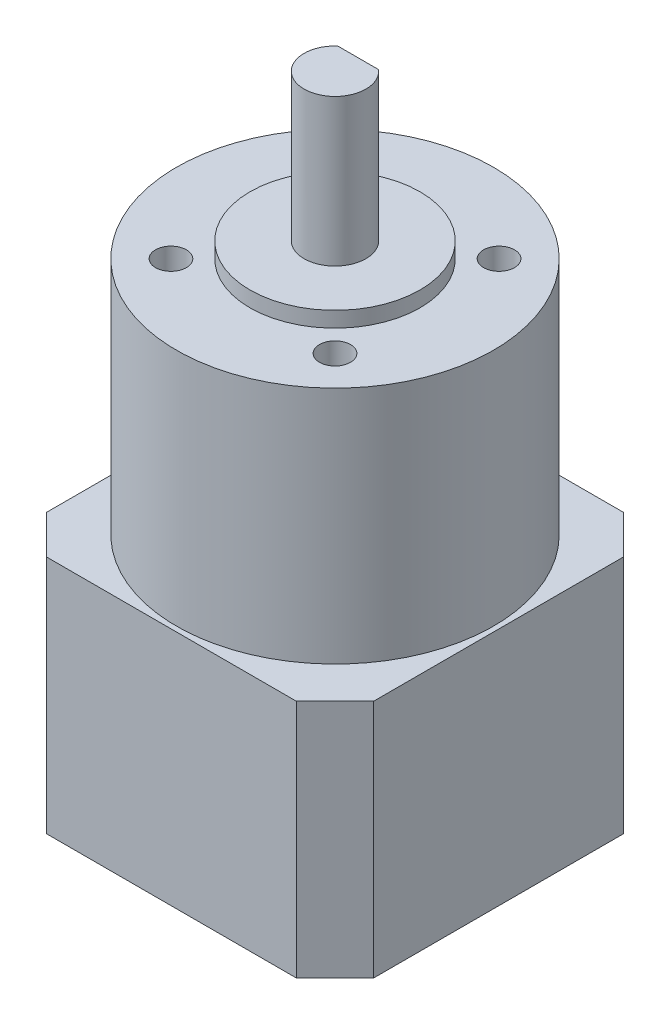
SolidWorks part; units mm, degrees
ref_plane "前视基准面" through (0, 0, 0) normal (0, 0, 1) x (1, 0, 0)
ref_plane "上视基准面" through (0, 0, 0) normal (0, 1, 0) x (1, 0, 0)
ref_plane "右视基准面" through (0, 0, 0) normal (1, 0, 0) x (0, 0, -1)
ref_plane "基准面1" through (0, -61.9, 0) normal (0, -1, 0) x (1, 0, 0)
sketch "草图1" plane through (0, -61.9, 0) normal (0, -1, 0) x (1, 0, 0)
  line L0 (21.15, -21.15) -> (21.15, 21.15)
  line L1 (21.15, 21.15) -> (-21.15, 21.15)
  line L2 (-21.15, 21.15) -> (-21.15, -21.15)
  line L3 (-21.15, -21.15) -> (21.15, -21.15)
extrude "凸台-拉伸1" add sketch "草图1" against normal blind 31
sketch "草图2" plane through (0, -30.9, 0) normal (0, 1, 0) x (-1, 0, 0)
  circle A0 centre (0, 0) radius 20.5
extrude "凸台-拉伸2" add sketch "草图2" along normal blind 30.9
sketch "草图3" plane through (0, 0, 0) normal (0, 1, 0) x (-1, 0, 0)
  circle A0 centre (0, 0) radius 11
extrude "凸台-拉伸3" add sketch "草图3" along normal blind 2
sketch "草图4" plane through (0, 2, 0) normal (0, 1, 0) x (-1, 0, 0)
  circle A0 centre (0, 0) radius 4
extrude "凸台-拉伸4" add sketch "草图4" along normal blind 19
sketch "草图5" plane through (0, 21, 0) normal (0, 1, 0) x (-1, 0, 0)
  line L0 (2.6458, -3) -> (-2.6458, -3)
  arc A0 (-2.6458, -3) -> (2.6458, -3) centre (0, 0) ccw
extrude "切除-拉伸1" cut sketch "草图5" against normal blind 13
hole_wizard "Ø4.0 (4) 直径孔1" positions "草图7" profile "草图6" hole size "Ø4.0" standard "ANSI Metric"
sketch "草图7" plane through (0, 0, 0) normal (0, 1, 0) x (1, 0, 0)
  point P0 (-10.6066, -10.6066)
  point P1 (10.6066, -10.6066)
  point P2 (10.6066, 10.6066)
  point P3 (-10.6066, 10.6066)
sketch "草图6" plane through (-10.6066, 0, 10.6066) normal (1, 0, 0) x (0, 0, 1)
  line L0 (0, 0) -> (0, 5)
  line L1 (0, 5) -> (2, 5)
  line L2 (2, 5) -> (2, 0)
  line L5 (2, 0) -> (0, 0)
  line L10 (0, 5) -> (-2, 5) construction
  line L11 (0, -6.35) -> (0, 107.95) construction
  dimension "孔直径" = 4
  dimension "孔深度" = 5
  dimension "导头角度" = 180
chamfer "倒角1" distance 5 angle 45 4 edges at (-21.15, -46.4, 21.15) (21.15, -46.4, 21.15) (-21.15, -46.4, -21.15) (21.15, -46.4, -21.15)
